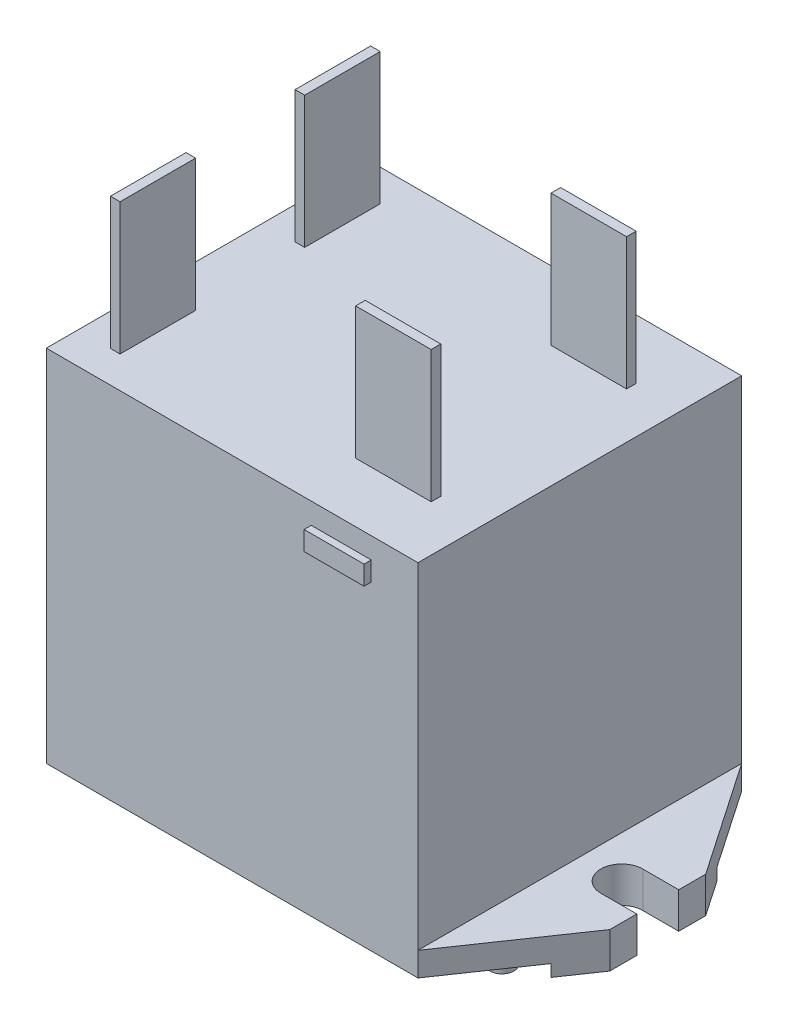
SolidWorks part; units mm, degrees
ref_plane "正面" through (0, 0, 0) normal (0, 0, 1) x (1, 0, 0)
ref_plane "平面" through (0, 0, 0) normal (0, 1, 0) x (1, 0, 0)
ref_plane "右側面" through (0, 0, 0) normal (1, 0, 0) x (0, 0, -1)
sketch "ｽｹｯﾁ1" plane through (0, 0, 0) normal (0, 1, 0) x (1, 0, 0)
  line L0 (-7.1576, 0) -> (45.1576, 0) construction
  line L1 (-3, 4) -> (-3, -4)
  line L2 (19, 15.9993) -> (19, -15.9993) construction
  line L3 (-3, -4) -> (3.5, -13.5)
  line L4 (3.5, -13.5) -> (34.5, -13.5)
  line L5 (34.5, -13.5) -> (41, -4)
  line L6 (41, -4) -> (41, 4)
  line L7 (41, 4) -> (34.5, 13.5)
  line L8 (34.5, 13.5) -> (3.5, 13.5)
  line L9 (3.5, 13.5) -> (-3, 4)
  circle A0 centre (0, 0) radius 1.75 construction
  circle A1 centre (38, 0) radius 1.75 construction
  dimension "D6" = 3.5
  dimension "D1" = 44
  dimension "D2" = 27
  dimension "D3" = 8
  dimension "D4" = 31
  dimension "D5" = 38
extrude "ﾍﾞｰｽ -押し出し" add sketch "ｽｹｯﾁ1" along normal blind 3
sketch "ｽｹｯﾁ2" plane through (0, 3, 0) normal (0, 1, 0) x (-1, 0, 0)
  line L0 (-45.1576, 0) -> (7.1576, 0) construction
  line L1 (-41, 4) -> (-41, -4) construction
  line L2 (-41, 1.75) -> (-38, 1.75)
  line L3 (-41, 1.75) -> (-41, -1.75)
  line L4 (-41, -1.75) -> (-38, -1.75)
  line L6 (3, -4) -> (3, 4) construction
  line L7 (3, 1.75) -> (0, 1.75)
  line L8 (3, 1.75) -> (3, -1.75)
  line L9 (3, -1.75) -> (0, -1.75)
  circle A0 centre (0, 0) radius 1.75 construction
  circle A1 centre (-38, 0) radius 1.75 construction
  arc A2 (0, 1.75) -> (0, -1.75) centre (0, 0) ccw
  arc A3 (-38, -1.75) -> (-38, 1.75) centre (-38, 0) ccw
extrude "ｶｯﾄ - 押し出し1" cut sketch "ｽｹｯﾁ2" against normal through all
sketch "ｽｹｯﾁ3" plane through (0, 0, 0) normal (0, -1, 0) x (1, 0, 0)
  line L30 (39, 6.9231) -> (39, 3.75)
  line L31 (41, -1.75) -> (41, -4) construction
  line L33 (34.5, 13.5) -> (41, 4) construction
  line L35 (3.5, 13.5) -> (34.5, 13.5) construction
  line L36 (39, -3.75) -> (39, -6.9231)
  line L37 (-3, 4) -> (3.5, 13.5) construction
  line L38 (3.5, -13.5) -> (-3, -4) construction
  line L39 (34.5, -13.5) -> (3.5, -13.5) construction
  line L40 (41, -4) -> (34.5, -13.5) construction
  line L41 (34.5, 13.5) -> (39, 6.9231)
  line L42 (0, -3.75) -> (-0.7477, -3.75)
  line L43 (-0.7477, -3.75) -> (4.5549, -11.5)
  line L44 (4.5549, -11.5) -> (33.4451, -11.5)
  line L45 (33.4451, -11.5) -> (38.7477, -3.75)
  line L46 (38.7477, -3.75) -> (38, -3.75)
  line L47 (38, 3.75) -> (38.7477, 3.75)
  line L48 (38.7477, 3.75) -> (33.4451, 11.5)
  line L49 (33.4451, 11.5) -> (4.5549, 11.5)
  line L50 (4.5549, 11.5) -> (-0.7477, 3.75)
  line L51 (-0.7477, 3.75) -> (0, 3.75)
  line L52 (0, -3.75) -> (-1, -3.75)
  line L53 (3.5, 13.5) -> (34.5, 13.5)
  line L54 (-1, 6.9231) -> (3.5, 13.5)
  line L55 (3.5, -13.5) -> (-1, -6.9231)
  line L56 (39, -3.75) -> (38, -3.75)
  line L57 (38, 3.75) -> (39, 3.75)
  line L58 (34.5, -13.5) -> (3.5, -13.5)
  line L59 (39, -6.9231) -> (34.5, -13.5)
  line L60 (-1, 6.9231) -> (-1, 3.75)
  line L61 (-1, 3.75) -> (0, 3.75)
  line L62 (-3, -4) -> (-3, -1.75) construction
  line L63 (-1, -3.75) -> (-1, -6.9231)
  arc A6 (38, 3.75) -> (38, -3.75) centre (38, 0) ccw
  arc A7 (0, -3.75) -> (0, 3.75) centre (0, 0) ccw
  arc A8 (38, 3.75) -> (38, -3.75) centre (38, 0) ccw
  arc A9 (0, -3.75) -> (0, 3.75) centre (0, 0) ccw
  dimension "D2" = 2
  dimension "D3" = 2
  dimension "D1" = 2
extrude "ｶｯﾄ - 押し出し2" cut sketch "ｽｹｯﾁ3" against normal blind 1
sketch "ｽｹｯﾁ4" plane through (0, 3, 0) normal (0, 1, 0) x (-1, 0, 0)
  line L0 (-19, -23.2985) -> (-19, 23.2985) construction
  line L1 (-34.5, -13.5) -> (-3.5, -13.5) construction
  line L2 (-3.5, -13.5) -> (-34.5, -13.5)
  line L3 (-3.5, -13.5) -> (-3.5, 13.5)
  line L4 (-3.5, 13.5) -> (-34.5, 13.5)
  line L5 (-34.5, -13.5) -> (-34.5, 13.5)
  line L6 (-3.5, 13.5) -> (-34.5, 13.5) construction
  dimension "D1" = 31
extrude "ﾎﾞｽ - 押し出し1" add sketch "ｽｹｯﾁ4" along normal blind 28
sketch "ｽｹｯﾁ5" plane through (0, 31, 0) normal (0, 1, 0) x (-1, 0, 0)
  line L0 (-19, -19.4723) -> (-19, 21.3854) construction
  line L1 (-3.5, -13.5) -> (-3.5, 13.5) construction
  line L2 (-34.5, 13.5) -> (-34.5, -13.5) construction
  line L3 (-41.5214, 0) -> (3.2437, 0) construction
  line L4 (-34.5, -13.5) -> (-3.5, -13.5) construction
  line L5 (-3.5, 13.5) -> (-34.5, 13.5) construction
  line L6 (-6.6, -11.3976) -> (-6.6, 9.5719) construction
  line L7 (-27.5, -9.2155) -> (-27.5, -3.7374) construction
  line L8 (-8.7974, 7.7) -> (-4.3563, 7.7) construction
  line L9 (-27.5, 4.2265) -> (-27.5, 9.5719) construction
  line L11 (-4.3563, -7.7) -> (-8.7974, -7.7) construction
  line L12 (-7, -10.85) -> (-6.2, -10.85)
  line L13 (-7, -10.85) -> (-7, -4.55)
  line L14 (-7, -4.55) -> (-6.2, -4.55)
  line L15 (-6.2, -10.85) -> (-6.2, -4.55)
  line L16 (-7, 4.55) -> (-6.2, 4.55)
  line L17 (-7, 4.55) -> (-7, 10.85)
  line L18 (-7, 10.85) -> (-6.2, 10.85)
  line L19 (-6.2, 4.55) -> (-6.2, 10.85)
  line L20 (-30.65, -8.55) -> (-24.35, -8.55)
  line L21 (-30.65, -8.55) -> (-30.65, -7.75)
  line L22 (-30.65, -7.75) -> (-24.35, -7.75)
  line L23 (-24.35, -8.55) -> (-24.35, -7.75)
  line L24 (-30.65, 7.75) -> (-24.35, 7.75)
  line L25 (-30.65, 7.75) -> (-30.65, 8.55)
  line L26 (-30.65, 8.55) -> (-24.35, 8.55)
  line L27 (-24.35, 7.75) -> (-24.35, 8.55)
  dimension "D1" = 20.9
  dimension "D2" = 8.5
  dimension "D3" = 15.4
  dimension "D4" = 6.3
  dimension "D5" = 0.8
  dimension "D6" = 6.3
  dimension "D7" = 0.8
  dimension "D8" = 15.5
extrude "ﾎﾞｽ - 押し出し2" add sketch "ｽｹｯﾁ5" along normal blind 11
sketch "ｽｹｯﾁ6" plane through (0, 0, 13.5) normal (0, 0, 1) x (1, 0, 0)
  line L0 (3.5, 31) -> (34.5, 31) construction
  line L1 (25.6, 29.25) -> (30.6, 29.25)
  line L2 (25.6, 29.25) -> (25.6, 27.65)
  line L3 (25.6, 27.65) -> (30.6, 27.65)
  line L4 (30.6, 29.25) -> (30.6, 27.65)
  line L5 (34.5, 31) -> (34.5, 3) construction
  dimension "D1" = 1.75
  dimension "D2" = 3.9
  dimension "D3" = 1.6
  dimension "D4" = 5
extrude "ﾎﾞｽ - 押し出し3" add sketch "ｽｹｯﾁ6" along normal blind 0.6
sketch "ｽｹｯﾁ7" plane through (0, 0, -13.5) normal (0, 0, -1) x (-1, 0, 0)
  line L0 (-34.5, 31) -> (-3.5, 31) construction
  line L1 (-12.4, 29.25) -> (-7.4, 29.25)
  line L2 (-12.4, 29.25) -> (-12.4, 27.65)
  line L3 (-12.4, 27.65) -> (-7.4, 27.65)
  line L4 (-7.4, 29.25) -> (-7.4, 27.65)
  line L5 (-3.5, 31) -> (-3.5, 3) construction
  dimension "D1" = 1.75
  dimension "D2" = 3.9
  dimension "D3" = 1.6
  dimension "D4" = 5
extrude "ﾎﾞｽ - 押し出し4" add sketch "ｽｹｯﾁ7" along normal blind 0.6
sketch "ｽｹｯﾁ8" plane through (0, 1, 0) normal (0, -1, 0) x (1, 0, 0)
  line L0 (0, 0) -> (39.0872, 0) construction
  line L2 (19, -20.1816) -> (19, 18.0798) construction
  circle A0 centre (19, 11.5) radius 1
  circle A1 centre (19, -11.5) radius 1
  circle A2 centre (36, 8) radius 1
  circle A3 centre (36, -8) radius 1
  circle A4 centre (2, 8) radius 1
  circle A5 centre (2, -8) radius 1
  dimension "D1" = 16
  dimension "D2" = 23
  dimension "D3" = 34
  dimension "D4" = 2
extrude "ﾎﾞｽ - 押し出し5" add sketch "ｽｹｯﾁ8" along normal up to surface (1 mm away)
